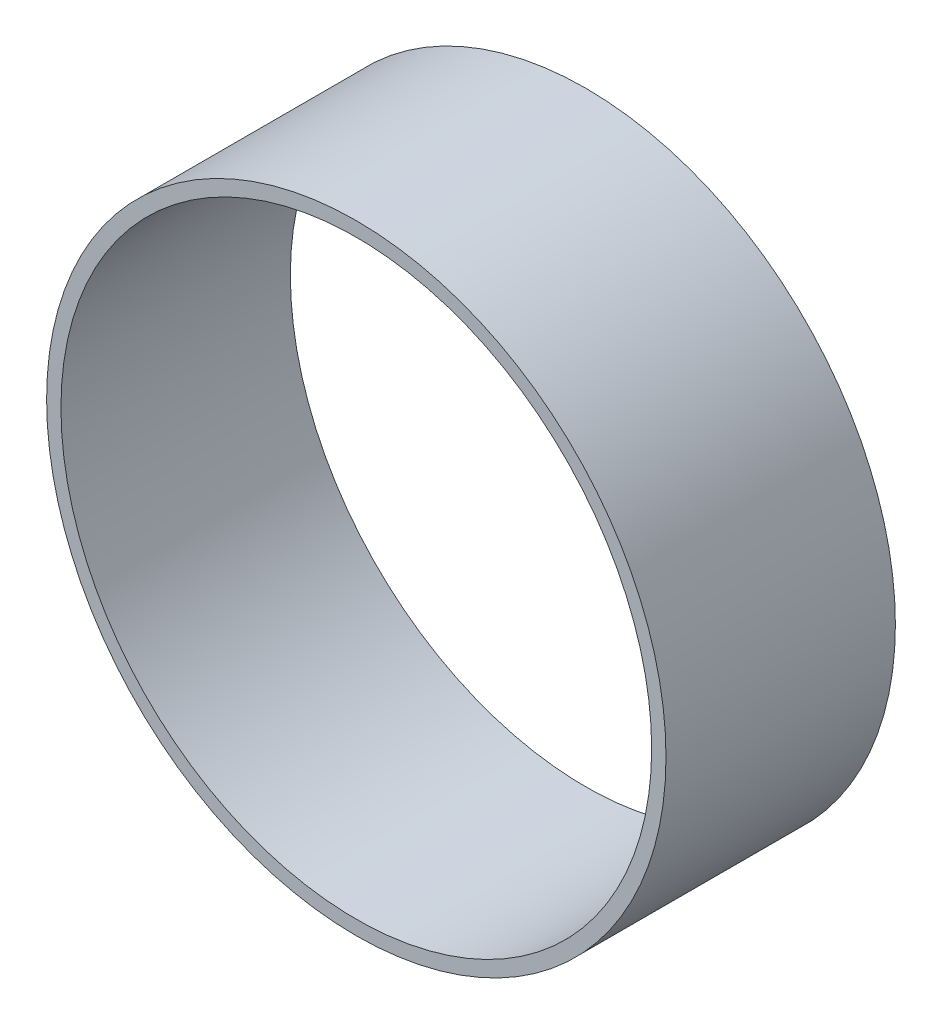
SolidWorks part; units mm, degrees
material "天然橡胶"
ref_plane "前视基准面" through (0, 0, 0) normal (0, 0, 1) x (1, 0, 0)
ref_plane "上视基准面" through (0, 0, 0) normal (0, 1, 0) x (1, 0, 0)
ref_plane "右视基准面" through (0, 0, 0) normal (1, 0, 0) x (0, 0, -1)
other "Configuration Table"
sketch "草图2" plane through (0, 0, 0) normal (0, 0, 1) x (1, 0, 0)
  circle A0 centre (0, 0) radius 25.75
  circle A1 centre (0, 0) radius 27
  dimension "D1" = 51.5
  dimension "D2" = 54
extrude "凸台-拉伸1" add sketch "草图2" along normal blind 20
